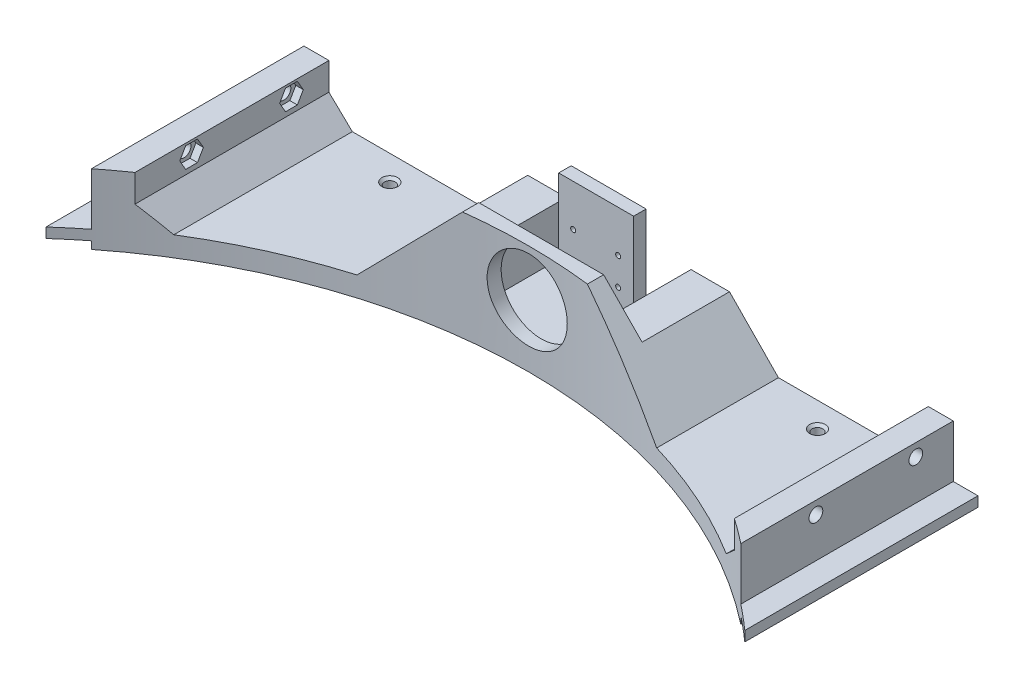
SolidWorks part; units mm, degrees
ref_plane "Front Plane" through (0, 0, 0) normal (0, 0, 1) x (1, 0, 0)
ref_plane "Top Plane" through (0, 0, 0) normal (0, 1, 0) x (1, 0, 0)
ref_plane "Right Plane" through (0, 0, 0) normal (1, 0, 0) x (0, 0, -1)
sketch "Sketch1" plane through (0, 0, 0) normal (0, 1, 0) x (1, 0, 0)
  line L0 (0, 0) -> (0, 650)
  line L1 (0, 650) -> (650, 650)
  line L2 (650, 650) -> (650, 0)
  line L3 (650, 0) -> (0, 0)
  dimension "D1" = 650
  dimension "D2" = 650
extrude "Boss-Extrude1" add sketch "Sketch1" along normal blind 8
sketch "Sketch3" plane through (0, 0, 0) normal (0, 0, 1) x (1, 0, 0)
  line L0 (325, 8) -> (325, 43.7071) construction
  line L1 (0, 8) -> (650, 8) construction
  line L2 (300, 43.7071) -> (350, 43.7071)
  line L3 (300, 43.7071) -> (265, 8)
  line L4 (265, 8) -> (385, 8)
  line L5 (385, 8) -> (350, 43.7071)
  point P7 (325, 43.7071)
  dimension "D1" = 50
  dimension "D2" = 50
  dimension "D3" = 50
  dimension "D4" = 120
extrude "Boss-Extrude2" add sketch "Sketch3" against normal blind 650
sketch "Sketch4" plane through (0, 0, 0) normal (0, 0, 1) x (1, 0, 0)
  line L0 (265, 8) -> (385, 8) construction
  circle A0 centre (325, 25) radius 16.05
  dimension "D1" = 17
  dimension "D2" = 32.1
extrude "Cut-Extrude2" cut sketch "Sketch4" against normal through all both and the other way through all
sketch "Sketch2" plane through (0, 8, 0) normal (0, 1, 0) x (1, 0, 0)
  line L0 (0, 650) -> (0, 0) construction
  line L1 (650, 650) -> (385, 650) construction
  circle A0 centre (325, 325) radius 210
  dimension "D3" = 420
  dimension "D1" = 325
  dimension "D2" = 325
extrude "Cut-Extrude1" cut sketch "Sketch2" against normal through all both and the other way through all
sketch "Sketch5" plane through (0, 0, 0) normal (0, 0, 1) x (1, 0, 0)
  line L0 (300, 43.7071) -> (350, 43.7071)
  line L1 (265, 8) -> (385, 8) construction
  line L2 (300, 8) -> (300, 28)
  line L3 (300, 8) -> (350, 8)
  line L4 (350, 8) -> (350, 28)
  line L5 (350, 28) -> (365.3961, 28)
  line L6 (385, 8) -> (350, 43.7071) construction
  line L7 (365.3961, 28) -> (350, 43.7071)
  line L8 (300, 28) -> (284.6039, 28)
  line L9 (300, 43.7071) -> (265, 8) construction
  line L10 (284.6039, 28) -> (300, 43.7071)
extrude "Cut-Extrude3" cut sketch "Sketch5" against normal blind 110 and the other way through all
sketch "Sketch6" plane through (0, 0, -650) normal (0, 0, -1) x (-1, 0, 0)
  line L0 (-265, 8) -> (-385, 8) construction
  line L1 (-350, 43.7071) -> (-300, 43.7071)
  line L2 (-300, 8) -> (-300, 28)
  line L3 (-300, 28) -> (-284.6039, 28)
  line L4 (-300, 43.7071) -> (-265, 8) construction
  line L5 (-284.6039, 28) -> (-300, 43.7071)
  line L6 (-350, 8) -> (-350, 28)
  line L7 (-350, 28) -> (-365.3961, 28)
  line L8 (-365.3961, 28) -> (-350, 43.7071)
  line L9 (-350, 8) -> (-300, 8)
extrude "Cut-Extrude4" cut sketch "Sketch6" against normal blind 110
sketch "Sketch7" plane through (0, 8, 0) normal (0, 1, 0) x (1, 0, 0)
  line L1 (325, 325) -> (325, 455) construction
  line L2 (325, 325) -> (325, 195) construction
  line L3 (325, 325) -> (455, 325) construction
  line L4 (325, 325) -> (195, 325) construction
  line L9 (325, 455) -> (455, 455) construction
  line L10 (455, 455) -> (455, 195) construction
  line L11 (455, 195) -> (195, 195) construction
  line L12 (195, 195) -> (195, 455) construction
  line L13 (195, 455) -> (325, 455) construction
  line L14 (195, 455) -> (195, 686.5445)
  line L15 (195, 686.5445) -> (455, 686.5445)
  line L16 (455, 686.5445) -> (455, 455)
  line L17 (455, 455) -> (195, 455)
  dimension "D1" = 130
  dimension "D2" = 130
  dimension "D3" = 130
  dimension "D4" = 130
extrude "Cut-Extrude5" cut sketch "Sketch7" against normal through all both and the other way through all flip side to cut
sketch "Sketch8" plane through (0, 0, -650) normal (0, 0, -1) x (-1, 0, 0)
  line L0 (-455, 8) -> (-455, 28)
  line L1 (-455, 28) -> (-445, 28)
  line L2 (-445, 28) -> (-445, 17)
  line L3 (-445, 17) -> (-435.6192, 8)
  line L4 (-455, 8) -> (-385, 8) construction
  line L5 (-435.6192, 8) -> (-455, 8)
  line L6 (-195, 8) -> (-195, 28)
  line L7 (-195, 28) -> (-205, 28)
  line L8 (-205, 28) -> (-205, 17)
  line L9 (-205, 17) -> (-214.3808, 8)
  line L10 (-265, 8) -> (-195, 8) construction
  line L11 (-214.3808, 8) -> (-195, 8)
  dimension "D1" = 20
  dimension "D2" = 10
  dimension "D3" = 13
  dimension "D4" = 20
  dimension "D5" = 10
  dimension "D6" = 13
  dimension "D7" = 11
  dimension "D8" = 11
extrude "Boss-Extrude3" add sketch "Sketch8" against normal blind 170
sketch "Sketch9" plane through (0, 0, -650) normal (0, 0, -1) x (-1, 0, 0)
  line L0 (-455, 7) -> (-464.9, 7)
  line L1 (-455, 0) -> (-455, 28) construction
  line L2 (-464.9, 7) -> (-464.9, 3)
  line L3 (-464.9, 3) -> (-455, 3)
  line L4 (-455, 3) -> (-455, 7)
  line L5 (-455, 0) -> (-195, 0) construction
  line L6 (-195, 3) -> (-195, 7)
  line L7 (-195, 28) -> (-195, 0) construction
  line L8 (-195, 7) -> (-185.1, 7)
  line L9 (-185.1, 7) -> (-185.1, 3)
  line L10 (-185.1, 3) -> (-195, 3)
  dimension "D1" = 3
  dimension "D2" = 4
  dimension "D3" = 3
  dimension "D4" = 4
  dimension "D5" = 9.9
  dimension "D6" = 9.9
extrude "Boss-Extrude4" add sketch "Sketch9" against normal blind 170
sketch "Sketch10" plane through (0, 8, 0) normal (0, 1, 0) x (1, 0, 0)
  line L0 (0, 0) -> (0, 650) construction
  line L1 (0, 650) -> (650, 650) construction
  line L2 (650, 650) -> (0, 0) construction
  circle A0 centre (325, 325) radius 210
extrude "Cut-Extrude6" cut sketch "Sketch10" against normal through all both and the other way through all
sketch "Sketch11" plane through (0, 8, 0) normal (0, 1, 0) x (1, 0, 0)
  line L0 (310, 562) -> (340, 562)
  line L1 (340, 562) -> (340, 567)
  line L2 (340, 567) -> (310, 567)
  line L3 (310, 567) -> (310, 562)
  line L4 (350, 540) -> (300, 540) construction
  line L5 (300, 540) -> (300, 650) construction
  dimension "D1" = 22
  dimension "D2" = 5
  dimension "D3" = 30
  dimension "D4" = 10
extrude "Boss-Extrude5" add sketch "Sketch11" along normal blind 40
sketch "Sketch12" plane through (0, 8, 0) normal (0, 1, 0) x (1, 0, 0)
  line L0 (325, 650) -> (325, 575) construction
  line L1 (350, 650) -> (300, 650) construction
  line L2 (325, 650) -> (468.2446, 650)
  line L3 (468.2446, 650) -> (468.2446, 575)
  line L4 (468.2446, 575) -> (178.6913, 575)
  line L5 (178.6913, 575) -> (178.6913, 650)
  line L6 (178.6913, 650) -> (325, 650)
  dimension "D1" = 75
extrude "Cut-Extrude7" cut sketch "Sketch12" against normal through all both and the other way through all
sketch "Sketch13" plane through (205, 0, 0) normal (1, 0, 0) x (0, 0, -1)
  line L0 (489.9242, 28) -> (575, 28) construction
  line L1 (575, 28) -> (575, 7) construction
  circle A0 centre (520, 23) radius 2.75
  circle A1 centre (560, 23) radius 2.75
  dimension "D1" = 5.5
  dimension "D2" = 5.5
  dimension "D3" = 5
  dimension "D4" = 5
  dimension "D5" = 15
  dimension "D6" = 40
extrude "Cut-Extrude8" cut sketch "Sketch13" against normal blind 10
sketch "Sketch14" plane through (455, 0, 0) normal (1, 0, 0) x (0, 0, -1)
  line L0 (575, 28) -> (575, 7) construction
  line L1 (489.9242, 28) -> (575, 28) construction
  circle A0 centre (560, 23) radius 2.75
  circle A1 centre (520, 23) radius 2.75
  dimension "D1" = 5.5
  dimension "D2" = 5.5
  dimension "D3" = 15
  dimension "D4" = 5
  dimension "D5" = 40
  dimension "D6" = 5
extrude "Cut-Extrude9" cut sketch "Sketch14" against normal blind 10
sketch "Sketch15" plane through (205, 0, 0) normal (1, 0, 0) x (0, 0, -1)
  line L0 (560, 23) -> (560, 27.1) construction
  line L1 (560, 23) -> (560, 18.9) construction
  line L2 (557.6329, 27.1) -> (562.3671, 27.1)
  line L3 (557.6329, 18.9) -> (562.3671, 18.9)
  line L4 (557.6329, 27.1) -> (555.2657, 23)
  line L5 (555.2657, 23) -> (557.6329, 18.9)
  line L6 (564.7343, 23) -> (562.3671, 18.9)
  line L7 (564.7343, 23) -> (562.3671, 27.1)
  point P7 (560, 27.1)
  point P10 (560, 18.9)
  dimension "D1" = 120
extrude "Cut-Extrude10" cut sketch "Sketch15" against normal blind 3
pattern_linear "LPattern1" count 2 spacing 40 along (0, 0, 1) of "Cut-Extrude10"
sketch "Sketch16" plane through (445, 0, 0) normal (-1, 0, 0) x (0, 0, 1)
  line L0 (-520, 23) -> (-520, 27.1) construction
  line L1 (-520, 23) -> (-520, 18.9) construction
  line L2 (-522.3671, 27.1) -> (-517.6329, 27.1)
  line L3 (-522.3671, 18.9) -> (-517.6329, 18.9)
  line L4 (-517.6329, 27.1) -> (-515.2657, 23)
  line L5 (-515.2657, 23) -> (-517.6329, 18.9)
  line L6 (-522.3671, 18.9) -> (-524.7343, 23)
  line L7 (-524.7343, 23) -> (-522.3671, 27.1)
  point P7 (-520, 27.1)
  point P10 (-520, 18.9)
  dimension "D1" = 120
extrude "Cut-Extrude11" cut sketch "Sketch16" against normal blind 3
pattern_linear "LPattern2" count 2 spacing 40 along (0, 0, -1) of "Cut-Extrude11"
sketch "Sketch17" plane through (0, 8, 0) normal (0, 1, 0) x (1, 0, 0)
  line L0 (435.6192, 575) -> (385, 575) construction
  line L1 (265, 575) -> (214.3808, 575) construction
  line L2 (214.3808, 503.5032) -> (214.3808, 575) construction
  line L3 (435.6192, 503.5032) -> (435.6192, 575) construction
  circle A0 centre (239.3808, 565) radius 2.15
  circle A1 centre (410.6192, 565) radius 2.15
  dimension "D1" = 4.3
  dimension "D2" = 4.3
  dimension "D3" = 10
  dimension "D4" = 10
  dimension "D5" = 25
  dimension "D6" = 25
extrude "Cut-Extrude12" cut sketch "Sketch17" against normal blind 10
chamfer "Chamfer1" distance 1 angle 45 3 edges at (239.3808, 8, -562.85) (239.3808, 0, -567.15) (410.6192, 8, -562.85)
sketch "Sketch18" plane through (0, 0, 0) normal (0, -1, 0) x (-1, 0, 0)
  line L0 (-294.9, 562) -> (-355, 562)
  line L1 (-355, 562) -> (-355, 546.9)
  line L2 (-355, 546.9) -> (-294.9, 546.9)
  line L3 (-294.9, 546.9) -> (-294.9, 562)
  line L4 (-455, 489.9242) -> (-455, 575) construction
  line L6 (-195, 575) -> (-455, 575) construction
  dimension "D1" = 60.1
  dimension "D2" = 100
  dimension "D3" = 15.1
  dimension "D4" = 13
extrude "Cut-Extrude13" cut sketch "Sketch18" against normal blind 3
sketch "Sketch19" plane through (0, 0, -562) normal (0, 0, 1) x (1, 0, 0)
  line L0 (350, 8) -> (300, 8) construction
  line L1 (310, 48) -> (310, 8) construction
  circle A0 centre (315.81, 20.26) radius 1
  circle A1 centre (333.81, 20.26) radius 1
  circle A2 centre (333.81, 31.26) radius 1
  circle A3 centre (315.81, 31.26) radius 1
  dimension "D1" = 2
  dimension "D6" = 2
  dimension "D11" = 2
  dimension "D12" = 2
  dimension "D2" = 12.26
  dimension "D3" = 5.81
  dimension "D4" = 5.81
  dimension "D5" = 11
  dimension "D7" = 12.26
  dimension "D8" = 18
  dimension "D9" = 18
  dimension "D10" = 11
extrude "Cut-Extrude14" cut sketch "Sketch19" against normal blind 10
